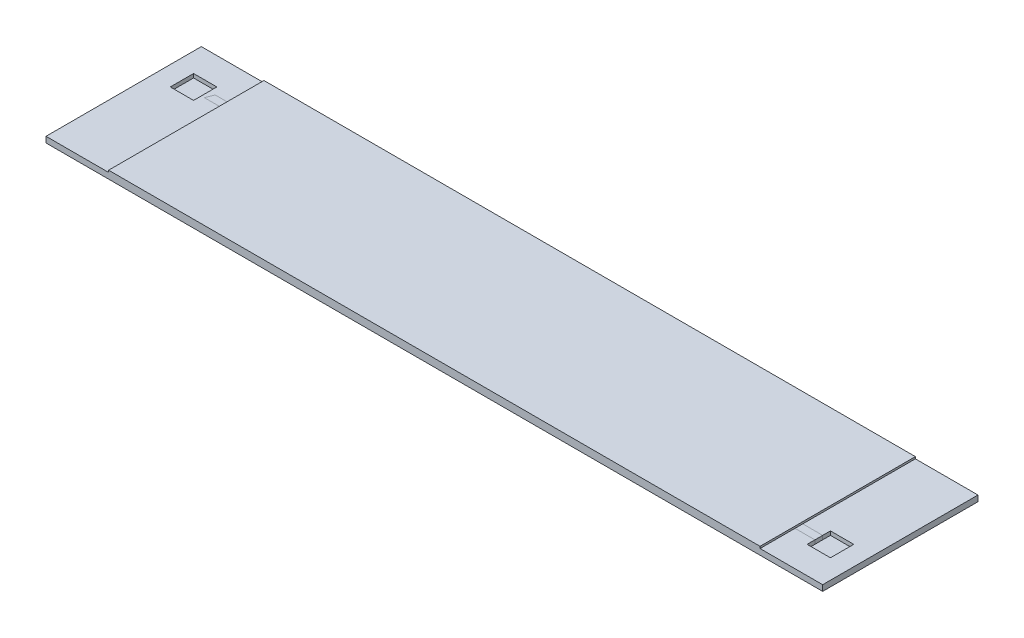
SolidWorks part; units mm, degrees
ref_plane "Front Plane" through (0, 0, 0) normal (0, 0, 1) x (1, 0, 0)
ref_plane "Top Plane" through (0, 0, 0) normal (0, 1, 0) x (1, 0, 0)
ref_plane "Right Plane" through (0, 0, 0) normal (1, 0, 0) x (0, 0, -1)
sketch "Sketch1" plane through (0, 0, 0) normal (0, 1, 0) x (1, 0, 0)
  line L0 (-40, 5) -> (40, 5)
  line L1 (-50, -10) -> (50, -10)
  line L2 (-50, -10) -> (-50, 10)
  line L3 (-50, 10) -> (50, 10)
  line L4 (50, -10) -> (50, 10)
  line L5 (40, 5) -> (40, 0)
  line L6 (40, 0) -> (-40, 0)
  line L7 (-40, 0) -> (-40, -5)
  line L8 (-40, -5) -> (40, -5)
  line L9 (-40, 5) -> (-46, 5)
  line L10 (40, -5) -> (46, -5)
  line L12 (-47.5, 3.5) -> (-44.5, 3.5) construction
  line L13 (-47.5, 3.5) -> (-47.5, 6.5) construction
  line L14 (-47.5, 6.5) -> (-44.5, 6.5) construction
  line L15 (-44.5, 3.5) -> (-44.5, 6.5) construction
  line L16 (-47.5, 3.5) -> (-44.5, 6.5) construction
  line L17 (-47.5, 6.5) -> (-44.5, 3.5) construction
  line L18 (44.5, -6.5) -> (47.5, -6.5) construction
  line L19 (44.5, -6.5) -> (44.5, -3.5) construction
  line L20 (44.5, -3.5) -> (47.5, -3.5) construction
  line L21 (47.5, -6.5) -> (47.5, -3.5) construction
  line L22 (44.5, -6.5) -> (47.5, -3.5) construction
  line L23 (44.5, -3.5) -> (47.5, -6.5) construction
  point P0 (0, 0)
  point P22 (0, 0)
  dimension "D1" = 20
  dimension "D2" = 100
  dimension "D3" = 5
  dimension "D4" = 5
  dimension "D5" = 80
  dimension "D6" = 6
  dimension "D7" = 6
  dimension "D8" = 3
  dimension "D9" = 3
  dimension "D10" = 3
  dimension "D11" = 3
extrude "Boss-Extrude1" add sketch "Sketch1" along normal mid plane 1
ref_plane "Plane1" through (40, 0, 0) normal (1, 0, 0) x (0, 0, -1)
sketch "Sketch2" plane through (40, 0, 0) normal (1, 0, 0) x (0, 0, -1)
  line L1 (-5.5, -0.25) -> (-4.5, -0.25)
  line L2 (-5.5, -0.25) -> (-5.5, 0.25)
  line L3 (-5.5, 0.25) -> (-4.5, 0.25)
  line L4 (-4.5, -0.25) -> (-4.5, 0.25)
  line L5 (-5.5, -0.25) -> (-4.5, 0.25) construction
  line L6 (-5.5, 0.25) -> (-4.5, -0.25) construction
  point P0 (-5, 0)
  dimension "D1" = 0.5
  dimension "D2" = 1
sketch3d "3DSketch1"
  line L0 (-40, 0, 5) -> (40, 0, 5) construction
  line L1 (-40, 0, 0) -> (-40, 0, 5) construction
  line L2 (40, 0, 0) -> (-40, 0, 0) construction
  line L3 (40, 0, -5) -> (40, 0, 0) construction
  line L4 (-40, 0, -5) -> (40, 0, -5) construction
  line L5 (-40, 0, 5) -> (40, 0, 5)
  line L6 (-40, 0, 0) -> (-40, 0, 5)
  line L7 (40, 0, 0) -> (-40, 0, 0)
  line L8 (40, 0, -5) -> (40, 0, 0)
  line L9 (-40, 0, -5) -> (40, 0, -5)
  line L10 (40, 0, 5) -> (46, 0, 5) construction
  line L11 (40, 0, 5) -> (46, 0, 5)
  line L12 (-40, 0, -5) -> (-46, 0, -5) construction
  line L13 (-40, 0, -5) -> (-46, 0, -5)
sweep "Sweep2" add profiles "Sketch2" path "3DSketch1"
sketch "Sketch4" plane through (0, 0.5, 0) normal (0, 1, 0) x (1, 0, 0)
  line L0 (-47.5, 6.5) -> (-44.5, 6.5) construction
  line L1 (-44.5, 3.5) -> (-44.5, 6.5) construction
  line L2 (-47.5, 3.5) -> (-44.5, 3.5) construction
  line L3 (-47.5, 3.5) -> (-47.5, 6.5) construction
  line L4 (44.5, -6.5) -> (44.5, -3.5) construction
  line L5 (44.5, -3.5) -> (47.5, -3.5) construction
  line L6 (47.5, -6.5) -> (47.5, -3.5) construction
  line L7 (44.5, -6.5) -> (47.5, -6.5) construction
  line L8 (-47.5, 6.5) -> (-44.5, 6.5)
  line L9 (-44.5, 3.5) -> (-44.5, 6.5)
  line L10 (-47.5, 3.5) -> (-44.5, 3.5)
  line L11 (-47.5, 3.5) -> (-47.5, 6.5)
  line L12 (44.5, -6.5) -> (44.5, -3.5)
  line L13 (44.5, -3.5) -> (47.5, -3.5)
  line L14 (47.5, -6.5) -> (47.5, -3.5)
  line L15 (44.5, -6.5) -> (47.5, -6.5)
extrude "Cut-Extrude1" cut sketch "Sketch4" against normal blind 0.75
sketch "Sketch5" plane through (0, 0.5, 0) normal (0, 1, 0) x (1, 0, 0)
  line L0 (-50, 10) -> (50, 10) construction
  line L1 (50, -10) -> (44.5, -10)
  line L2 (50, -10) -> (50, 10)
  line L3 (50, 10) -> (44.5, 10)
  line L4 (44.5, -10) -> (44.5, 10)
  line L5 (44.5, -6.5) -> (44.5, -3.5) construction
  line L6 (-50, -10) -> (-44.5, -10)
  line L7 (-50, -10) -> (-50, 10)
  line L8 (-50, 10) -> (-44.5, 10)
  line L9 (-44.5, -10) -> (-44.5, 10)
  dimension "D1" = 5.5
extrude "Cut-Extrude2" cut sketch "Sketch5" against normal blind 0.25
sketch "Sketch6" plane through (0, 0.5, 0) normal (0, 1, 0) x (1, 0, 0)
  line L0 (-44.5, 10) -> (44.5, 10) construction
  line L1 (41.9377, -10) -> (-41.9377, -10)
  line L2 (41.9377, -10) -> (41.9377, 10)
  line L3 (41.9377, 10) -> (-41.9377, 10)
  line L4 (-41.9377, -10) -> (-41.9377, 10)
  line L5 (41.9377, -10) -> (-41.9377, 10) construction
  line L6 (41.9377, 10) -> (-41.9377, -10) construction
  point P0 (0, 0)
  line M5 (-44.5, 10) -> (-44.5, -10)
  line M6 (-44.5, -10) -> (44.5, -10)
  line M7 (44.5, -10) -> (44.5, 10)
  line M8 (44.5, 10) -> (-44.5, 10)
extrude "Cut-Extrude3" cut sketch "Sketch6" against normal blind 0.25 contours L4 M6 M8 M5 | L2 M6 M7 M8
